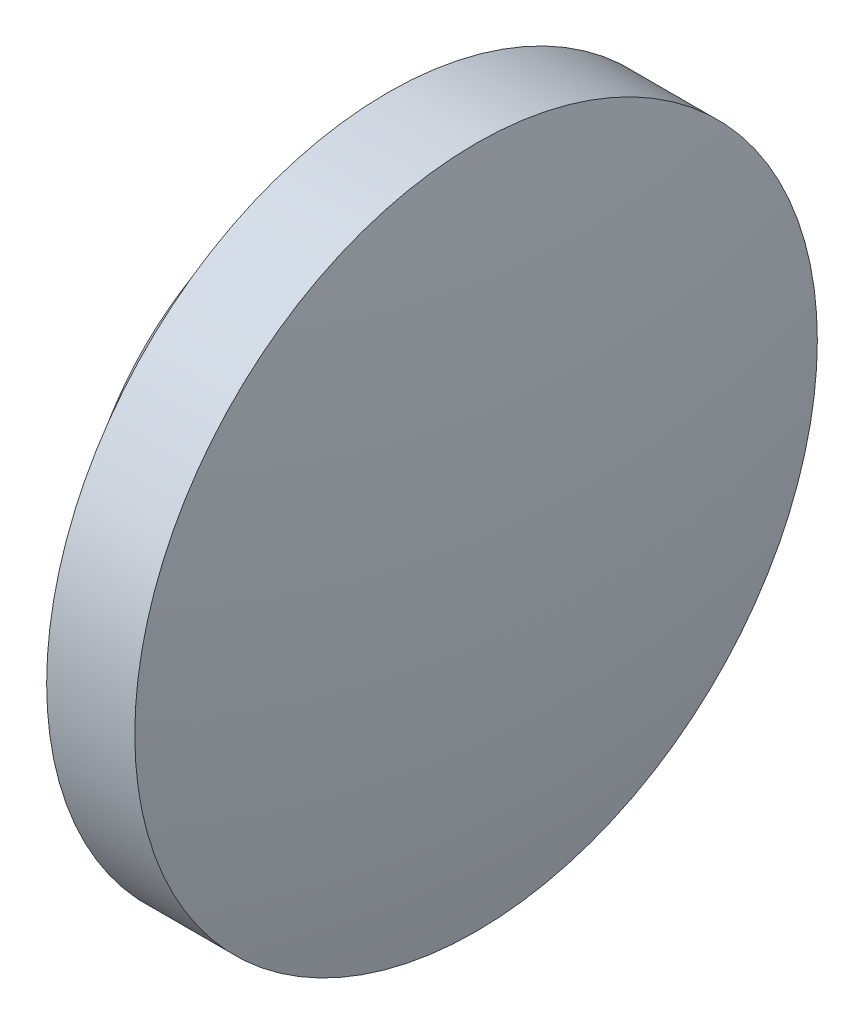
SolidWorks part; units mm, degrees
material "Glass"
ref_plane "Front Plane" through (0, 0, 0) normal (0, 0, 1) x (1, 0, 0)
ref_plane "Top Plane" through (0, 0, 0) normal (0, 1, 0) x (1, 0, 0)
ref_plane "Right Plane" through (0, 0, 0) normal (1, 0, 0) x (0, 0, -1)
sketch "Sketch1" plane through (0, 0, 0) normal (0, 0, 1) x (1, 0, 0)
  line L0 (0, 0) -> (-97.9139, 0) construction
  line L1 (-2.655, 7.5) -> (-0.7186, 7.5)
  line L2 (-6.38, 0) -> (0, 0)
  arc A0 (-0.7186, 7.5) -> (0, 0) centre (-39.5, 0) cw
  spline S0 degree 3 poles (-2.655, 7.5) (-3.0041, 6.9935) (-3.6073, 6.1611) (-4.4604, 5.0156) (-5.1284, 4.0265) (-5.6832, 3.0299) (-6.2083, 1.7111) (-6.383, 0.6787) (-6.38, 0) knots 0 0 0 0 0.216367 0.361524 0.502322 0.635901 0.761914 1 1 1 1
  point P0 (-6.38, 0)
  point P7 (-6.302, 1)
  point P8 (-6.065, 2)
  point P9 (-5.671, 3)
  point P10 (-5.125, 4)
  point P11 (-4.46, 5)
  point P12 (-3.73, 6)
  point P13 (-3.005, 7)
  dimension "D1" = 7.5
  dimension "D2" = 39.5
  dimension "D3" = 6.38
  dimension "D4" = 0.078
  dimension "D5" = 1
  dimension "D6" = 2
  dimension "D7" = 3
  dimension "D8" = 4
  dimension "D9" = 5
  dimension "D10" = 6
  dimension "D11" = 7
  dimension "D12" = 3.725
  dimension "D13" = 0.315
  dimension "D14" = 0.709
  dimension "D15" = 1.255
  dimension "D16" = 1.92
  dimension "D17" = 2.65
  dimension "D18" = 3.375
revolve "Revolve1" add sketch "Sketch1" angle 360 about L0
